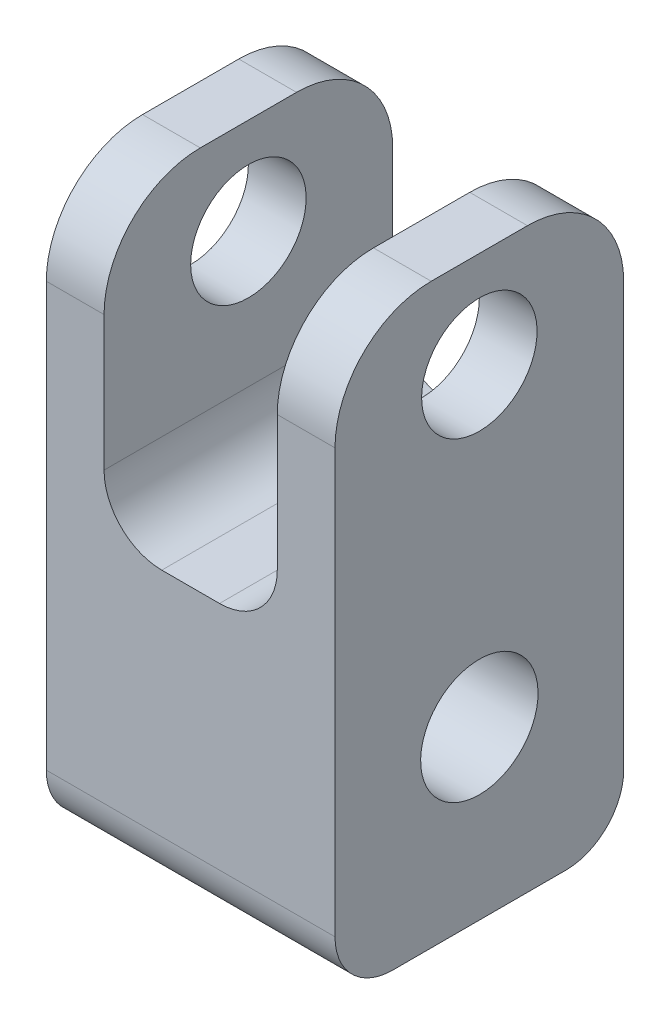
SolidWorks part; units mm, degrees
ref_plane "Front Plane" through (0, 0, 0) normal (0, 0, 1) x (1, 0, 0)
ref_plane "Top Plane" through (0, 0, 0) normal (0, 1, 0) x (1, 0, 0)
ref_plane "Right Plane" through (0, 0, 0) normal (1, 0, 0) x (0, 0, -1)
sketch "Sketch2" plane through (0, 0, 0) normal (0, 0, 1) x (1, 0, 0)
  line L1 (-15, 15) -> (15, 15)
  line L2 (-15, 15) -> (-15, -15)
  line L3 (-15, -15) -> (15, -15)
  line L4 (15, 15) -> (15, -15)
  line L5 (-15, 15) -> (15, -15) construction
  line L6 (-15, -15) -> (15, 15) construction
  point P0 (0, 0)
  dimension "D1" = 30
  dimension "D2" = 30
extrude "Boss-Extrude2" add sketch "Sketch2" along normal blind 30
sketch "Sketch4" plane through (0, 15, 0) normal (0, 1, 0) x (1, 0, 0)
  line L0 (-15, -30) -> (-9, -30)
  line L1 (15, -30) -> (-15, -30) construction
  line L2 (-9, -30) -> (-9, 0)
  line L3 (15, 0) -> (-15, 0) construction
  line L4 (-9, 0) -> (-15, 0)
  line L5 (-15, 0) -> (-15, -30)
  line L6 (9, -30) -> (15, -30)
  line L7 (15, -30) -> (15, 0)
  line L8 (15, 0) -> (9, 0)
  line L9 (9, 0) -> (9, -30)
  dimension "D1" = 6
  dimension "D2" = 6
extrude "Boss-Extrude3" add sketch "Sketch4" along normal blind 30
fillet "Fillet4" radius 10 4 edges at (12, 45, 30) (12, 45, 0) (-12, 45, 0) (-12, 45, 30)
sketch "Sketch5" plane through (-15, 0, 0) normal (-1, 0, 0) x (0, 0, 1)
  circle A0 centre (15, 35) radius 6
  dimension "D1" = 12
extrude "Cut-Extrude1" cut sketch "Sketch5" against normal blind 30
fillet "Fillet5" radius 6 2 edges at (9, 15, 15) (-9, 15, 15)
sketch "Sketch6" plane through (-15, 0, 0) normal (-1, 0, 0) x (0, 0, 1)
  circle A0 centre (15, 2.3843) radius 6.1
  dimension "D1" = 12.2
extrude "Cut-Extrude2" cut sketch "Sketch6" against normal blind 62
fillet "Fillet6" radius 6 2 edges at (0, -15, 0) (0, -15, 30)
